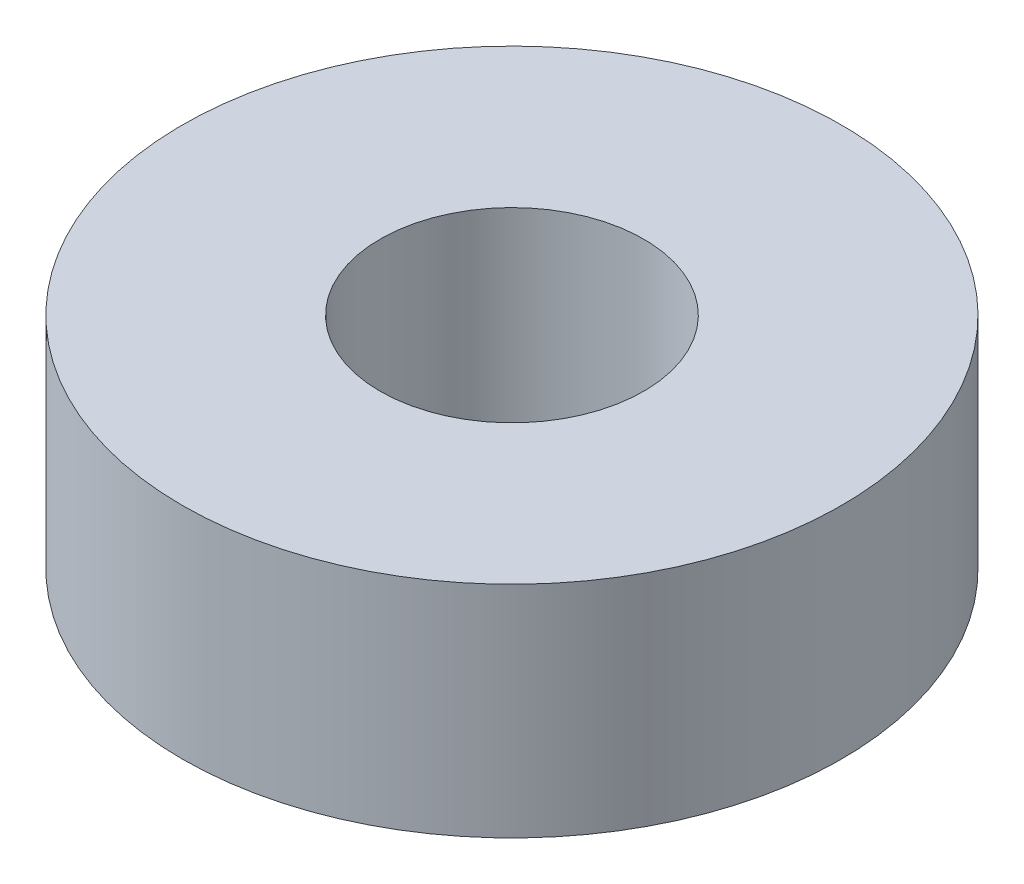
SolidWorks part; units mm, degrees
ref_plane "前视基准面" through (0, 0, 0) normal (0, 0, 1) x (1, 0, 0)
ref_plane "上视基准面" through (0, 0, 0) normal (0, 1, 0) x (1, 0, 0)
ref_plane "右视基准面" through (0, 0, 0) normal (1, 0, 0) x (0, 0, -1)
other "Configuration Table"
sketch "草图1" plane through (0, 0, 0) normal (0, 1, 0) x (1, 0, 0)
  circle A0 centre (0, 0) radius 7.5
  circle A1 centre (0, 0) radius 3
  dimension "D1" = 6
  dimension "D2" = 15
extrude "凸台-拉伸1" add sketch "草图1" along normal blind 5
